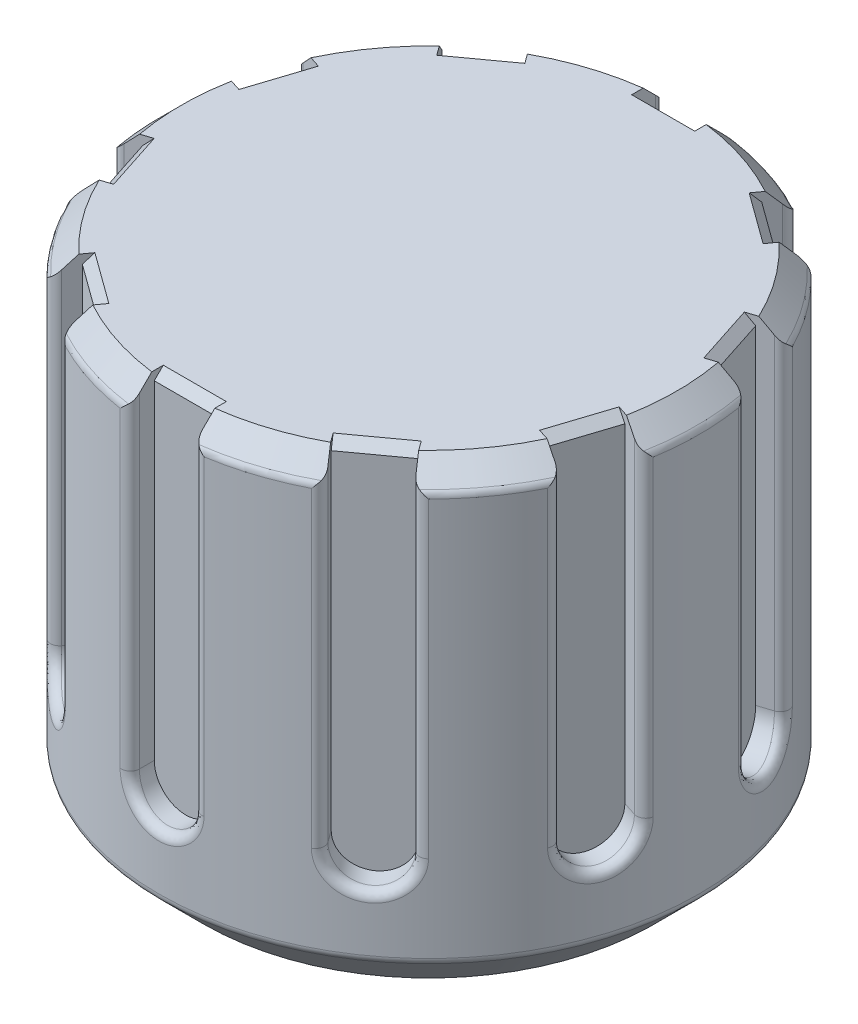
SolidWorks part; units mm, degrees
ref_plane "前视基准面" through (0, 0, 0) normal (0, 0, 1) x (1, 0, 0)
ref_plane "上视基准面" through (0, 0, 0) normal (0, 1, 0) x (1, 0, 0)
ref_plane "右视基准面" through (0, 0, 0) normal (1, 0, 0) x (0, 0, -1)
sketch "草图1" plane through (0, 0, 0) normal (0, 1, 0) x (1, 0, 0)
  circle A0 centre (0, 0) radius 6
  dimension "D1" = 12
extrude "凸台-拉伸1" add sketch "草图1" along normal blind 11
sketch "草图2" plane through (0, 0, 0) normal (0, -1, 0) x (1, 0, 0)
  circle A0 centre (0, 0) radius 3.75
  dimension "D1" = 7.5
extrude "切除-拉伸1" cut sketch "草图2" against normal blind 2.5
sketch "草图4" plane through (0, 0, 0) normal (0, -1, 0) x (1, 0, 0)
  circle A0 centre (0, 0) radius 3.1
  dimension "D1" = 6.2
extrude "切除-拉伸2" cut sketch "草图4" against normal blind 8.5
sketch "草图5" plane through (0, 11, 0) normal (0, 1, 0) x (1, 0, 0)
  circle A0 centre (0, 0) radius 13.5
  dimension "D1" = 27
extrude "切除-拉伸3" cut sketch "草图5" against normal blind 0.5
chamfer "倒角1" distance 0.5 angle 45 1 edges at (0, 10.5, 6)
sketch "草图6" plane through (0, 0, 0) normal (0, 0, 1) x (1, 0, 0)
  line L0 (0, 43) -> (0, 3) construction
  line L1 (0.7, 43) -> (0.7, 3)
  line L2 (-0.7, 43) -> (-0.7, 3)
  arc A0 (0.7, 43) -> (-0.7, 43) centre (0, 43) ccw
  arc A1 (-0.7, 3) -> (0.7, 3) centre (0, 3) ccw
  point P2 (0, 23)
  dimension "D1" = 1.4
  dimension "D2" = 40
  dimension "D3" = 3
extrude "切除-拉伸4" cut sketch "草图6" against normal blind 4 from offset 5.4 offset against normal yes
pattern_circular "阵列(圆周)1" count 10 every 36 about axis through (0, 0, 0) along (0, 1, 0) of "切除-拉伸4"
chamfer "倒角2" distance 0.2 angle 45 10 edges at (5.1357, 10.5, 1.6687) (3.174, 10.5, 4.3687) (0, 10.5, 5.4) (-3.174, 10.5, 4.3687) (-5.1357, 10.5, 1.6687) (-5.1357, 10.5, -1.6687) (-3.174, 10.5, -4.3687) (5.1357, 10.5, -1.6687) (3.174, 10.5, -4.3687) (0, 10.5, -5.4)
chamfer "倒角3" distance 0.4 angle 45 1 edges at (0, 0, -3.75)
chamfer "倒角4" distance 1 angle 45 1 edges at (0, 0, 6)
fillet "圆角4" radius 0.2 41 edges at (0.0788, 2.3044, -5.9995) (-0.7, 6.5, -5.959) (0.7, 6.5, -5.959) (-3.5267, 2.3, -4.8541) (-4.0689, 6.5, -4.4095) (-2.9363, 6.5, -5.2324) (3.6514, 3.6825, -4.761) (2.9363, 6.5, -5.2324) (4.0689, 6.5, -4.4095) (5.7064, 2.3, -1.8541) (5.4511, 6.5, -2.5072) (5.8837, 6.5, -1.1757) (5.6564, 3.6825, 2.0014) (5.8837, 6.5, 1.1757) (5.4511, 6.5, 2.5072) (3.3997, 3.6825, 4.9439) (4.0689, 6.5, 4.4095) (2.9363, 6.5, 5.2324) (-0.1556, 3.6825, 5.998) (0.7, 6.5, 5.959) (-0.7, 6.5, 5.959) (-3.6514, 3.6825, 4.761) (-2.9363, 6.5, 5.2324) (-4.0689, 6.5, 4.4095) (-5.7525, 3.6825, 1.7055) (-5.4511, 6.5, 2.5072) (-5.8837, 6.5, 1.1757) (-5.6564, 3.6825, -2.0014) (-5.8837, 6.5, -1.1757) (-5.4511, 6.5, -2.5072) (-6, 10, 0) (-4.8541, 10, 3.5267) (-1.8541, 10, 5.7063) (1.8541, 10, 5.7063) (4.8541, 10, 3.5267) (6, 10, 0) (4.8541, 10, -3.5267) (-4.8541, 10, -3.5267) (-1.8541, 10, -5.7063) (1.8541, 10, -5.7063) (0, 1, 6)
